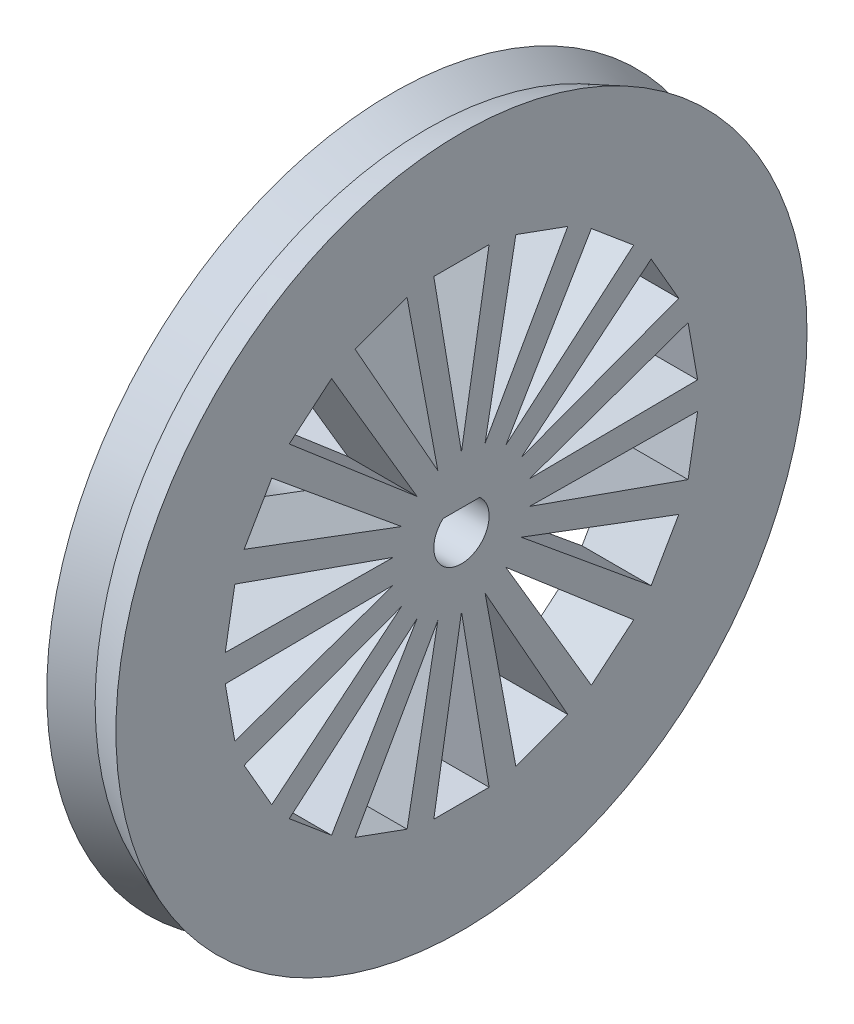
SolidWorks part; units mm, degrees
ref_plane "Front Plane" through (0, 0, 0) normal (0, 0, 1) x (1, 0, 0)
ref_plane "Top Plane" through (0, 0, 0) normal (0, 1, 0) x (1, 0, 0)
ref_plane "Right Plane" through (0, 0, 0) normal (1, 0, 0) x (0, 0, -1)
sketch "Sketch4" plane through (0, 0, 0) normal (0, 1, 0) x (1, 0, 0)
  line L0 (0, 0) -> (0, 25)
  line L1 (0, 25) -> (2.5, 24)
  line L2 (2.5, 24) -> (5, 25)
  line L3 (5, 25) -> (5, 0)
  line L4 (5, 0) -> (0, 0)
  line L5 (2.5, 24) -> (5, 24) construction
  line L6 (2.5, 24) -> (0, 24) construction
  point P8 (2.5, 11.7396)
  dimension "D1" = 5
  dimension "D2" = 25
  dimension "D3" = 24
revolve "Revolve1" add sketch "Sketch4" angle 360 about L4
sketch "Sketch5" plane through (0, 0, 0) normal (-1, 0, 0) x (0, 0, 1)
  line L0 (-1.3229, 1.5) -> (1.3229, 1.5)
  line L1 (-4.7492, -2) -> (5.4082, -2) construction
  line L2 (-2, 17) -> (0, 5)
  line L3 (0, 5) -> (2, 17)
  line L4 (2, 17) -> (-2, 17)
  line L5 (0, 2) -> (0, 25) construction
  line L6 (7.6937, 15.2907) -> (3.935, 16.6588)
  line L7 (3.935, 16.6588) -> (1.7101, 4.6985)
  line L8 (1.7101, 4.6985) -> (7.6937, 15.2907)
  line L9 (12.4595, 11.7372) -> (9.3953, 14.3083)
  line L10 (9.3953, 14.3083) -> (3.2139, 3.8302)
  line L11 (3.2139, 3.8302) -> (12.4595, 11.7372)
  line L12 (15.7224, 6.7679) -> (13.7224, 10.2321)
  line L13 (13.7224, 10.2321) -> (4.3301, 2.5)
  line L14 (4.3301, 2.5) -> (15.7224, 6.7679)
  line L15 (17.089, 0.9824) -> (16.3944, 4.9216)
  line L16 (16.3944, 4.9216) -> (4.924, 0.8682)
  line L17 (4.924, 0.8682) -> (17.089, 0.9824)
  line L18 (16.3944, -4.9216) -> (17.089, -0.9824)
  line L19 (17.089, -0.9824) -> (4.924, -0.8682)
  line L20 (4.924, -0.8682) -> (16.3944, -4.9216)
  line L21 (13.7224, -10.2321) -> (15.7224, -6.7679)
  line L22 (15.7224, -6.7679) -> (4.3301, -2.5)
  line L23 (4.3301, -2.5) -> (13.7224, -10.2321)
  line L24 (9.3953, -14.3083) -> (12.4595, -11.7372)
  line L25 (12.4595, -11.7372) -> (3.2139, -3.8302)
  line L26 (3.2139, -3.8302) -> (9.3953, -14.3083)
  line L27 (3.935, -16.6588) -> (7.6937, -15.2907)
  line L28 (7.6937, -15.2907) -> (1.7101, -4.6985)
  line L29 (1.7101, -4.6985) -> (3.935, -16.6588)
  line L30 (-2, -17) -> (2, -17)
  line L31 (2, -17) -> (0, -5)
  line L32 (0, -5) -> (-2, -17)
  line L33 (-7.6937, -15.2907) -> (-3.935, -16.6588)
  line L34 (-3.935, -16.6588) -> (-1.7101, -4.6985)
  line L35 (-1.7101, -4.6985) -> (-7.6937, -15.2907)
  line L36 (-12.4595, -11.7372) -> (-9.3953, -14.3083)
  line L37 (-9.3953, -14.3083) -> (-3.2139, -3.8302)
  line L38 (-3.2139, -3.8302) -> (-12.4595, -11.7372)
  line L39 (-15.7224, -6.7679) -> (-13.7224, -10.2321)
  line L40 (-13.7224, -10.2321) -> (-4.3301, -2.5)
  line L41 (-4.3301, -2.5) -> (-15.7224, -6.7679)
  line L42 (-17.089, -0.9824) -> (-16.3944, -4.9216)
  line L43 (-16.3944, -4.9216) -> (-4.924, -0.8682)
  line L44 (-4.924, -0.8682) -> (-17.089, -0.9824)
  line L45 (-16.3944, 4.9216) -> (-17.089, 0.9824)
  line L46 (-17.089, 0.9824) -> (-4.924, 0.8682)
  line L47 (-4.924, 0.8682) -> (-16.3944, 4.9216)
  line L48 (-13.7224, 10.2321) -> (-15.7224, 6.7679)
  line L49 (-15.7224, 6.7679) -> (-4.3301, 2.5)
  line L50 (-4.3301, 2.5) -> (-13.7224, 10.2321)
  line L51 (-9.3953, 14.3083) -> (-12.4595, 11.7372)
  line L52 (-12.4595, 11.7372) -> (-3.2139, 3.8302)
  line L53 (-3.2139, 3.8302) -> (-9.3953, 14.3083)
  line L54 (-3.935, 16.6588) -> (-7.6937, 15.2907)
  line L55 (-7.6937, 15.2907) -> (-1.7101, 4.6985)
  line L56 (-1.7101, 4.6985) -> (-3.935, 16.6588)
  line L57 (0, 0) -> (0, 5) construction
  line L58 (0, 0) -> (1.7101, 4.6985) construction
  line L59 (0, 0) -> (2, 0) construction
  line L60 (0, 0) -> (-2, 0) construction
  arc A0 (-1.3229, 1.5) -> (1.3229, 1.5) centre (0, 0) ccw
  circle A1 centre (0, 0) radius 25 construction
  point P1 (0, 2.5167)
  point P14 (0, 17)
  point P17 (0, 2.1361)
  point P71 (0, 2.328)
  point P72 (0, 0)
  dimension "D1" = 2
  dimension "D2" = 3.5
  dimension "D3" = 4
  dimension "D4" = 3
  dimension "D5" = 8
  dimension "D7" = 20
  dimension "D8" = 1.5
  dimension "D6" = 18
extrude "Cut-Extrude1" cut sketch "Sketch5" against normal through all contours L49 L50 L48 | L52 L53 L51 | L55 L56 L54 | L3 L4 L2 | L7 L8 L6 | L10 L11 L9 | L13 L14 L12 | L16 L17 L15 | L19 L20 L18 | L22 L23 L21 | L25 L26 L24 | L28 L29 L27 | L31 L32 L30 | L34 L35 L33 | L37 L38 L36 | L40 L41 L39 | L43 L44 L42 | A0 L0 | L45 L46 L47
sketch "Sketch6" plane through (0, 0, 0) normal (-1, 0, 0) x (0, 0, 1)
  line L0 (-1.3229, 1.5) -> (1.3229, 1.5) construction
  line L1 (-1.3229, 1.5) -> (1.3229, 1.5)
  line L2 (-3.5707, 3.5) -> (3.5707, 3.5)
  arc A0 (-1.3229, 1.5) -> (1.3229, 1.5) centre (0, 0) ccw construction
  arc A1 (-1.3229, 1.5) -> (1.3229, 1.5) centre (0, 0) ccw
  arc A2 (-3.5707, 3.5) -> (3.5707, 3.5) centre (0, 0) ccw
  dimension "D1" = 3
  dimension "D2" = 2
extrude "Boss-Extrude1" add sketch "Sketch6" along normal blind 5 contours A2 L2 | L1 A1
sketch "Sketch7" plane through (0, 3.5, 0) normal (0, 1, 0) x (1, 0, 0)
  line L0 (0, 0) -> (-5, 0) construction
  line L1 (0, 3.5707) -> (0, -3.5707) construction
  line L2 (-5, 3.5707) -> (-5, -3.5707) construction
  circle A0 centre (-3, 0) radius 0.75
  point P8 (-2.9264, 0)
  dimension "D1" = 1.5
  dimension "D2" = 2
extrude "Cut-Extrude2" cut sketch "Sketch7" against normal blind 3
